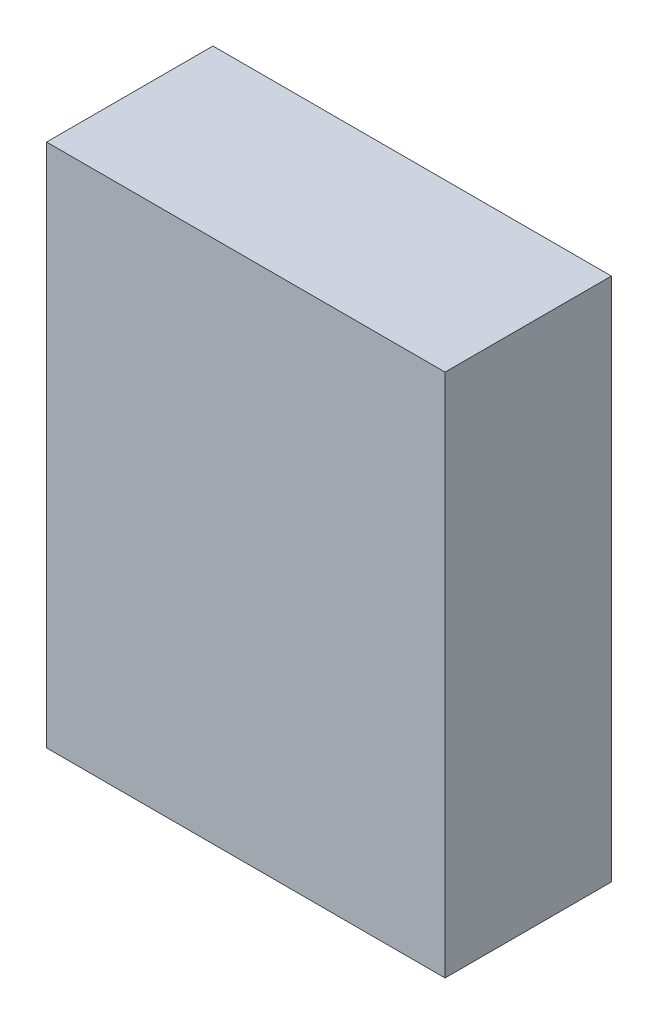
SolidWorks part; units mm, degrees
ref_plane "Front Plane" through (0, 0, 0) normal (0, 0, 1) x (1, 0, 0)
ref_plane "Top Plane" through (0, 0, 0) normal (0, 1, 0) x (1, 0, 0)
ref_plane "Right Plane" through (0, 0, 0) normal (1, 0, 0) x (0, 0, -1)
sketch "Sketch1" plane through (0, 0, 0) normal (0, 0, 1) x (1, 0, 0)
  line L1 (-26.35, -34.7) -> (26.35, -34.7)
  line L2 (-26.35, -34.7) -> (-26.35, 34.7)
  line L3 (-26.35, 34.7) -> (26.35, 34.7)
  line L4 (26.35, -34.7) -> (26.35, 34.7)
  line L5 (-26.35, -34.7) -> (26.35, 34.7) construction
  line L6 (-26.35, 34.7) -> (26.35, -34.7) construction
  point P0 (0, 0)
extrude "Envelope" add sketch "Sketch1" along normal blind 22
